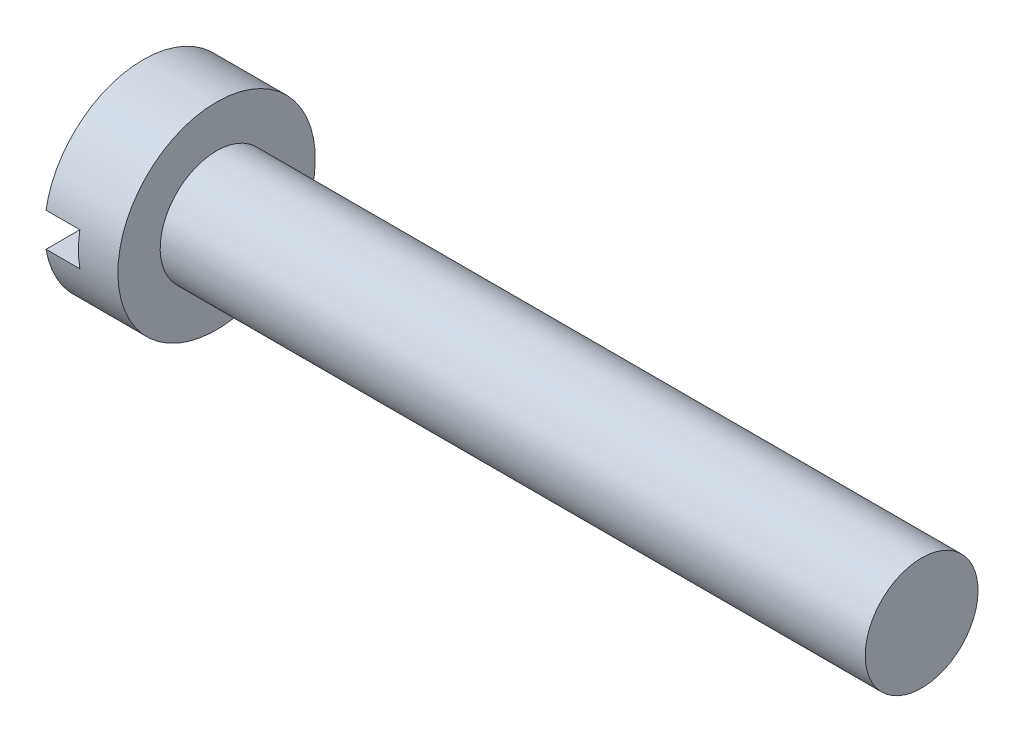
SolidWorks part; units mm, degrees
material "Plain Carbon Steel"
ref_plane "Front Plane" through (0, 0, 0) normal (0, 0, 1) x (1, 0, 0)
ref_plane "Top Plane" through (0, 0, 0) normal (0, 1, 0) x (1, 0, 0)
ref_plane "Right Plane" through (0, 0, 0) normal (1, 0, 0) x (0, 0, -1)
sketch "Sketch1" plane through (0, 0, 0) normal (0, 0, 1) x (1, 0, 0)
  line L0 (0, 0) -> (0, 3.5)
  line L1 (0, 3.5) -> (2.6, 3.5)
  line L2 (2.6, 3.5) -> (2.6, 2)
  line L3 (2.6, 2) -> (27.6, 2)
  line L4 (27.6, 2) -> (27.6, 0)
  line L5 (27.6, 0) -> (0, 0) construction
  line L6 (0, 0) -> (27.6, 0)
  dimension "D1" = 4
  dimension "D2" = 25
  dimension "D3" = 7
  dimension "D4" = 2.6
revolve "Revolve1" add sketch "Sketch1" angle 360 about L5
sketch "Sketch2" plane through (0, 0, 0) normal (-1, 0, 0) x (0, 0, 1)
  line L0 (3.5, 0) -> (-3.5, 0) construction
  line L1 (-3.5, 0.6) -> (3.5, 0.6)
  line L2 (-3.5, 0.6) -> (-3.5, -0.6)
  line L3 (-3.5, -0.6) -> (3.5, -0.6)
  line L4 (3.5, 0.6) -> (3.5, -0.6)
  circle A0 centre (0, 0) radius 3.5 construction
  dimension "D1" = 1.2
extrude "Cut-Extrude1" cut sketch "Sketch2" against normal blind 1.2
